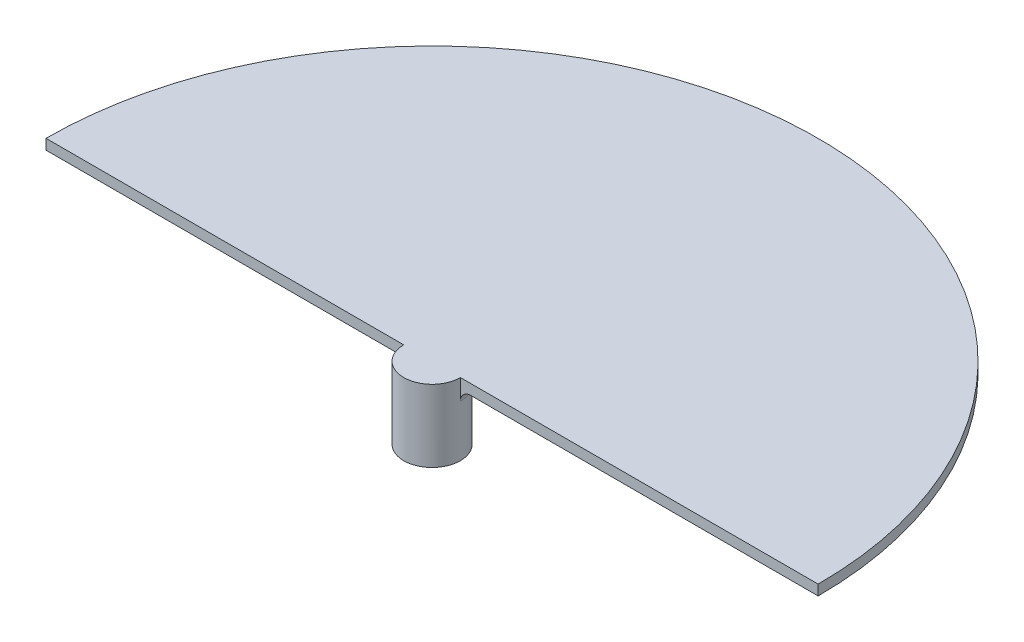
SolidWorks part; units mm, degrees
ref_plane "Front Plane" through (0, 0, 0) normal (0, 0, 1) x (1, 0, 0)
ref_plane "Top Plane" through (0, 0, 0) normal (0, 1, 0) x (1, 0, 0)
ref_plane "Right Plane" through (0, 0, 0) normal (1, 0, 0) x (0, 0, -1)
sketch "Sketch1" plane through (0, 0, 0) normal (0, 1, 0) x (1, 0, 0)
  line L0 (-37.5, 0) -> (37.5, 0)
  arc A0 (37.5, 0) -> (-37.5, 0) centre (0, 0) ccw
  dimension "D1" = 75
extrude "Boss-Extrude1" add sketch "Sketch1" along normal blind 1
sketch "Sketch3" plane through (0, 1, 0) normal (0, 1, 0) x (1, 0, 0)
  circle A0 centre (0, 0) radius 2.75
  dimension "D1" = 5.5
extrude "Boss-Extrude2" add sketch "Sketch3" against normal blind 7
fillet "Fillet1" radius 1 1 edges at (0, 0, -2.75)
